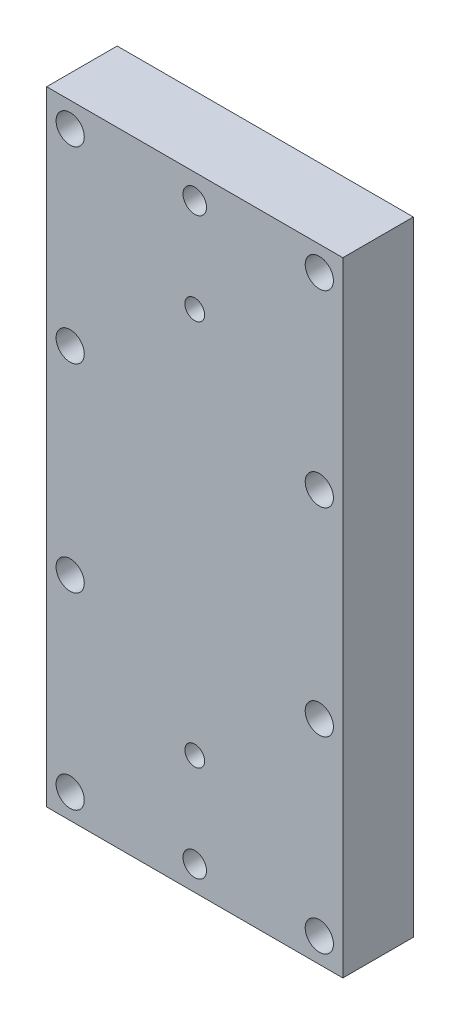
SolidWorks part; units mm, degrees
material "6061 Alloy"
ref_plane "Front Plane" through (0, 0, 0) normal (0, 0, 1) x (1, 0, 0)
ref_plane "Top Plane" through (0, 0, 0) normal (0, 1, 0) x (1, 0, 0)
ref_plane "Right Plane" through (0, 0, 0) normal (1, 0, 0) x (0, 0, -1)
sketch "Sketch1" plane through (0, 0, 0) normal (0, 0, 1) x (1, 0, 0)
  line L0 (-155.4665, 24.25) -> (-155.4665, -24.25) construction
  line L1 (-155.4665, -24.25) -> (-154.4665, -25.25) construction
  line L2 (-154.4665, -25.25) -> (-145.4847, -25.25) construction
  line L3 (-145.4847, -25.25) -> (-145.4847, -38.6) construction
  line L4 (-145.4847, -38.6) -> (-102.4482, -38.6) construction
  line L5 (-102.4482, -38.6) -> (-102.4482, -25.25) construction
  line L6 (-102.4482, -25.25) -> (-93.4665, -25.25) construction
  line L7 (-93.4665, -25.25) -> (-92.4665, -24.25) construction
  line L8 (-92.4665, -24.25) -> (-92.4665, 24.25) construction
  line L9 (-92.4665, 24.25) -> (-93.4665, 25.25) construction
  line L10 (-93.4665, 25.25) -> (-102.4482, 25.25) construction
  line L11 (-102.4482, 25.25) -> (-102.4482, 38.6) construction
  line L12 (-102.4482, 38.6) -> (-145.4847, 38.6) construction
  line L13 (-145.4847, 38.6) -> (-145.4847, 25.25) construction
  line L14 (-145.4847, 25.25) -> (-154.4665, 25.25) construction
  line L15 (-154.4665, 25.25) -> (-155.4665, 24.25) construction
  line L16 (-155.4665, 106.45) -> (-155.4665, 57.95) construction
  line L17 (-155.4665, 57.95) -> (-154.4665, 56.95) construction
  line L18 (-154.4665, 56.95) -> (-145.4847, 56.95) construction
  line L19 (-145.4847, 56.95) -> (-145.4847, 43.6) construction
  line L20 (-145.4847, 43.6) -> (-102.4482, 43.6) construction
  line L21 (-102.4482, 43.6) -> (-102.4482, 56.95) construction
  line L22 (-102.4482, 56.95) -> (-93.4665, 56.95) construction
  line L23 (-93.4665, 56.95) -> (-92.4665, 57.95) construction
  line L24 (-92.4665, 57.95) -> (-92.4665, 106.45) construction
  line L25 (-92.4665, 106.45) -> (-93.4665, 107.45) construction
  line L26 (-93.4665, 107.45) -> (-102.4482, 107.45) construction
  line L27 (-102.4482, 107.45) -> (-102.4482, 120.8) construction
  line L28 (-102.4482, 120.8) -> (-145.4847, 120.8) construction
  line L29 (-145.4847, 120.8) -> (-145.4847, 107.45) construction
  line L30 (-145.4847, 107.45) -> (-154.4665, 107.45) construction
  line L31 (-154.4665, 107.45) -> (-155.4665, 106.45) construction
  line L32 (-31.5, 106.45) -> (-31.5, 57.95) construction
  line L33 (-31.5, 57.95) -> (-30.5, 56.95) construction
  line L34 (-30.5, 56.95) -> (-21.5182, 56.95) construction
  line L35 (-21.5182, 56.95) -> (-21.5182, 43.6) construction
  line L36 (-21.5182, 43.6) -> (21.5182, 43.6) construction
  line L37 (21.5182, 43.6) -> (21.5182, 56.95) construction
  line L38 (21.5182, 56.95) -> (30.5, 56.95) construction
  line L39 (30.5, 56.95) -> (31.5, 57.95) construction
  line L40 (31.5, 57.95) -> (31.5, 106.45) construction
  line L41 (31.5, 106.45) -> (30.5, 107.45) construction
  line L42 (30.5, 107.45) -> (21.5182, 107.45) construction
  line L43 (21.5182, 107.45) -> (21.5182, 120.8) construction
  line L44 (21.5182, 120.8) -> (-21.5182, 120.8) construction
  line L45 (-21.5182, 120.8) -> (-21.5182, 107.45) construction
  line L46 (-21.5182, 107.45) -> (-30.5, 107.45) construction
  line L47 (-30.5, 107.45) -> (-31.5, 106.45) construction
  line L48 (-31.5, 24.25) -> (-31.5, -24.25) construction
  line L49 (-31.5, -24.25) -> (-30.5, -25.25) construction
  line L50 (-30.5, -25.25) -> (-21.5182, -25.25) construction
  line L51 (-21.5182, -25.25) -> (-21.5182, -38.6) construction
  line L52 (-21.5182, -38.6) -> (21.5182, -38.6) construction
  line L53 (21.5182, -38.6) -> (21.5182, -25.25) construction
  line L54 (21.5182, -25.25) -> (30.5, -25.25) construction
  line L55 (30.5, -25.25) -> (31.5, -24.25) construction
  line L56 (31.5, -24.25) -> (31.5, 24.25) construction
  line L57 (31.5, 24.25) -> (30.5, 25.25) construction
  line L58 (30.5, 25.25) -> (21.5182, 25.25) construction
  line L59 (21.5182, 25.25) -> (21.5182, 38.6) construction
  line L60 (21.5182, 38.6) -> (-21.5182, 38.6) construction
  line L61 (-21.5182, 38.6) -> (-21.5182, 25.25) construction
  line L62 (-21.5182, 25.25) -> (-30.5, 25.25) construction
  line L63 (-30.5, 25.25) -> (-31.5, 24.25) construction
  line L64 (-155.4665, 24.25) -> (-155.4665, -24.25) construction
  line L65 (-155.4665, -24.25) -> (-154.4665, -25.25) construction
  line L66 (-154.4665, -25.25) -> (-145.4847, -25.25) construction
  line L67 (-145.4847, -25.25) -> (-145.4847, -38.6) construction
  line L68 (-145.4847, -38.6) -> (-102.4482, -38.6) construction
  line L69 (-102.4482, -38.6) -> (-102.4482, -25.25) construction
  line L70 (-102.4482, -25.25) -> (-93.4665, -25.25) construction
  line L71 (-93.4665, -25.25) -> (-92.4665, -24.25) construction
  line L72 (-92.4665, -24.25) -> (-92.4665, 24.25) construction
  line L73 (-92.4665, 24.25) -> (-93.4665, 25.25) construction
  line L74 (-93.4665, 25.25) -> (-102.4482, 25.25) construction
  line L75 (-102.4482, 25.25) -> (-102.4482, 38.6) construction
  line L76 (-102.4482, 38.6) -> (-145.4847, 38.6) construction
  line L77 (-145.4847, 38.6) -> (-145.4847, 25.25) construction
  line L78 (-145.4847, 25.25) -> (-154.4665, 25.25) construction
  line L79 (-154.4665, 25.25) -> (-155.4665, 24.25) construction
  line L80 (-155.4665, 106.45) -> (-155.4665, 57.95) construction
  line L81 (-155.4665, 57.95) -> (-154.4665, 56.95) construction
  line L82 (-154.4665, 56.95) -> (-145.4847, 56.95) construction
  line L83 (-145.4847, 56.95) -> (-145.4847, 43.6) construction
  line L84 (-145.4847, 43.6) -> (-102.4482, 43.6) construction
  line L85 (-102.4482, 43.6) -> (-102.4482, 56.95) construction
  line L86 (-102.4482, 56.95) -> (-93.4665, 56.95) construction
  line L87 (-93.4665, 56.95) -> (-92.4665, 57.95) construction
  line L88 (-92.4665, 57.95) -> (-92.4665, 106.45) construction
  line L89 (-92.4665, 106.45) -> (-93.4665, 107.45) construction
  line L90 (-93.4665, 107.45) -> (-102.4482, 107.45) construction
  line L91 (-102.4482, 107.45) -> (-102.4482, 120.8) construction
  line L92 (-102.4482, 120.8) -> (-145.4847, 120.8) construction
  line L93 (-145.4847, 120.8) -> (-145.4847, 107.45) construction
  line L94 (-145.4847, 107.45) -> (-154.4665, 107.45) construction
  line L95 (-154.4665, 107.45) -> (-155.4665, 106.45) construction
  line L96 (-31.5, 106.45) -> (-31.5, 57.95) construction
  line L97 (-31.5, 57.95) -> (-30.5, 56.95) construction
  line L98 (-30.5, 56.95) -> (-21.5182, 56.95) construction
  line L99 (-21.5182, 56.95) -> (-21.5182, 43.6) construction
  line L100 (-21.5182, 43.6) -> (21.5182, 43.6) construction
  line L101 (21.5182, 43.6) -> (21.5182, 56.95) construction
  line L102 (21.5182, 56.95) -> (30.5, 56.95) construction
  line L103 (30.5, 56.95) -> (31.5, 57.95) construction
  line L104 (31.5, 57.95) -> (31.5, 106.45) construction
  line L105 (31.5, 106.45) -> (30.5, 107.45) construction
  line L106 (30.5, 107.45) -> (21.5182, 107.45) construction
  line L107 (21.5182, 107.45) -> (21.5182, 120.8) construction
  line L108 (21.5182, 120.8) -> (-21.5182, 120.8) construction
  line L109 (-21.5182, 120.8) -> (-21.5182, 107.45) construction
  line L110 (-21.5182, 107.45) -> (-30.5, 107.45) construction
  line L111 (-30.5, 107.45) -> (-31.5, 106.45) construction
  line L112 (-31.5, 24.25) -> (-31.5, -24.25) construction
  line L113 (-31.5, -24.25) -> (-30.5, -25.25) construction
  line L114 (-30.5, -25.25) -> (-21.5182, -25.25) construction
  line L115 (-21.5182, -25.25) -> (-21.5182, -38.6) construction
  line L116 (-21.5182, -38.6) -> (21.5182, -38.6) construction
  line L117 (21.5182, -38.6) -> (21.5182, -25.25) construction
  line L118 (21.5182, -25.25) -> (30.5, -25.25) construction
  line L119 (30.5, -25.25) -> (31.5, -24.25) construction
  line L120 (31.5, -24.25) -> (31.5, 24.25) construction
  line L121 (31.5, 24.25) -> (30.5, 25.25) construction
  line L122 (30.5, 25.25) -> (21.5182, 25.25) construction
  line L123 (21.5182, 25.25) -> (21.5182, 38.6) construction
  line L124 (21.5182, 38.6) -> (-21.5182, 38.6) construction
  line L125 (-21.5182, 38.6) -> (-21.5182, 25.25) construction
  line L126 (-21.5182, 25.25) -> (-30.5, 25.25) construction
  line L127 (-30.5, 25.25) -> (-31.5, 24.25) construction
  line L129 (31.5, 107.45) -> (-31.5, 107.45)
  line L130 (31.5, 107.45) -> (31.5, -25.25)
  line L131 (31.5, -25.25) -> (-31.5, -25.25)
  line L132 (-31.5, 107.45) -> (-31.5, -25.25)
  circle A0 centre (26.5, 102.2) radius 3
  circle A1 centre (-97.4665, 62.2) radius 2.5
  circle A2 centre (-97.4665, 62.2) radius 2.5 construction
  circle A3 centre (-97.4665, 102.2) radius 2.5
  circle A4 centre (-97.4665, 102.2) radius 2.5 construction
  circle A5 centre (-150.4665, 102.2) radius 2.5
  circle A6 centre (-150.4665, 102.2) radius 2.5 construction
  circle A7 centre (-150.4665, 62.2) radius 2.5
  circle A8 centre (-150.4665, 62.2) radius 2.5 construction
  circle A9 centre (26.5, 62.2) radius 2.5
  circle A10 centre (26.5, 62.2) radius 2.5 construction
  circle A11 centre (26.5, 102.2) radius 2.5
  circle A12 centre (26.5, 102.2) radius 2.5 construction
  circle A13 centre (-26.5, 102.2) radius 2.5
  circle A14 centre (-26.5, 102.2) radius 2.5 construction
  circle A15 centre (-26.5, 62.2) radius 2.5
  circle A16 centre (-26.5, 62.2) radius 2.5 construction
  circle A17 centre (-97.4665, -20) radius 2.5
  circle A18 centre (-97.4665, -20) radius 2.5 construction
  circle A19 centre (-97.4665, 20) radius 2.5
  circle A20 centre (-97.4665, 20) radius 2.5 construction
  circle A21 centre (-150.4665, 20) radius 2.5
  circle A22 centre (-150.4665, 20) radius 2.5 construction
  circle A23 centre (-150.4665, -20) radius 2.5
  circle A24 centre (-150.4665, -20) radius 2.5 construction
  circle A25 centre (26.5, -20) radius 2.5
  circle A26 centre (26.5, -20) radius 2.5 construction
  circle A27 centre (26.5, 20) radius 2.5
  circle A28 centre (26.5, 20) radius 2.5 construction
  circle A29 centre (-26.5, 20) radius 2.5
  circle A30 centre (-26.5, 20) radius 2.5 construction
  circle A31 centre (-26.5, -20) radius 2.5
  circle A32 centre (-26.5, -20) radius 2.5 construction
  circle A33 centre (26.5, 62.2) radius 3
  circle A34 centre (-26.5, 62.2) radius 3
  circle A35 centre (-26.5, 102.2) radius 3
  circle A36 centre (26.5, 20) radius 3
  circle A37 centre (26.5, -20) radius 3
  circle A38 centre (-26.5, -20) radius 3
  circle A39 centre (-26.5, 20) radius 3
  dimension "D17" = 6
  dimension "D18" = 6
  dimension "D19" = 6
  dimension "D20" = 6
  dimension "D21" = 6
  dimension "D22" = 6
  dimension "D23" = 6
  dimension "D24" = 6
  dimension "D1" = 0
  dimension "D2" = 0
  dimension "D3" = 0
  dimension "D4" = 0
  dimension "D5" = 0
  dimension "D6" = 0
  dimension "D7" = 0
  dimension "D8" = 0
  dimension "D9" = 0
  dimension "D10" = 0
  dimension "D11" = 0
  dimension "D12" = 0
  dimension "D13" = 0
  dimension "D14" = 0
  dimension "D15" = 0
  dimension "D16" = 0
extrude "Boss-Extrude1" add sketch "Sketch1" along normal up to surface (15 mm away) contours L129 L132 L131 L130 A39 A38 A37 A36 A35 A34 A33 A0
sketch "Sketch2" plane through (0, 0, 15) normal (0, 0, 1) x (1, 0, 0)
  line L0 (0, 107.45) -> (0, -25.25) construction
  line L1 (-31.5, 41.1) -> (31.5, 41.1) construction
  line L2 (-26.5, -20) -> (26.5, -20) construction
  line L4 (31.5, -25.25) -> (31.5, 107.45)
  line L5 (31.5, 107.45) -> (-31.5, 107.45)
  line L6 (-31.5, 107.45) -> (-31.5, -25.25)
  line L7 (-31.5, -25.25) -> (31.5, -25.25)
  line L8 (31.5, -25.25) -> (31.5, 107.45)
  line L9 (31.5, 107.45) -> (-31.5, 107.45)
  line L10 (-31.5, 107.45) -> (-31.5, -25.25)
  line L11 (-31.5, -25.25) -> (31.5, -25.25)
  circle A0 centre (0, 0) radius 2.1 construction
  circle A1 centre (0, 82.2) radius 2.1 construction
  circle A2 centre (0, 0) radius 2.1
  circle A3 centre (0, 82.2) radius 2.1
  point P16 (0, -20)
  point P20 (0, 102.2)
  dimension "D1" = 0
hole_wizard "setscrews" positions "3DSketch1" profile "Sketch3" tap size "M5x0.8" standard "ANSI Metric" end condition up to next
sketch3d "3DSketch1"
  point P0 (0, 82.2, 15)
  point P3 (0, 0, 15)
sketch "Sketch3" plane through (0, 82.2, 15) normal (1, 0, 0) x (0, -1, 0)
  line L0 (0, 0) -> (0, 15)
  line L1 (0, 15) -> (2.1, 15)
  line L2 (2.1, 15) -> (2.1, 0)
  line L5 (2.1, 0) -> (0, 0)
  line L11 (0, -6.35) -> (0, 107.95) construction
  dimension "Thru Tap Drill Dia." = 4.2
  dimension "Thru Tap Drill Depth" = 15
cosmetic thread "Hole Thread1" parameters "D2"=5
cosmetic thread "Hole Thread2" parameters "D2"=5
hole_wizard "screwHoles" positions "3DSketch2" profile "Sketch4" tap size "M6x1.0" standard "ANSI Metric" end condition up to next
sketch3d "3DSketch2"
  point P0 (0, 102.2, 15)
  point P3 (0, -20, 15)
sketch "Sketch4" plane through (0, 102.2, 15) normal (1, 0, 0) x (0, -1, 0)
  line L0 (0, 0) -> (0, 15)
  line L1 (0, 15) -> (2.5, 15)
  line L2 (2.5, 15) -> (2.5, 0)
  line L5 (2.5, 0) -> (0, 0)
  line L11 (0, -6.35) -> (0, 107.95) construction
  dimension "Thru Tap Drill Dia." = 5
  dimension "Thru Tap Drill Depth" = 15
cosmetic thread "Hole Thread3" parameters "D2"=6
cosmetic thread "Hole Thread4" parameters "D2"=6
